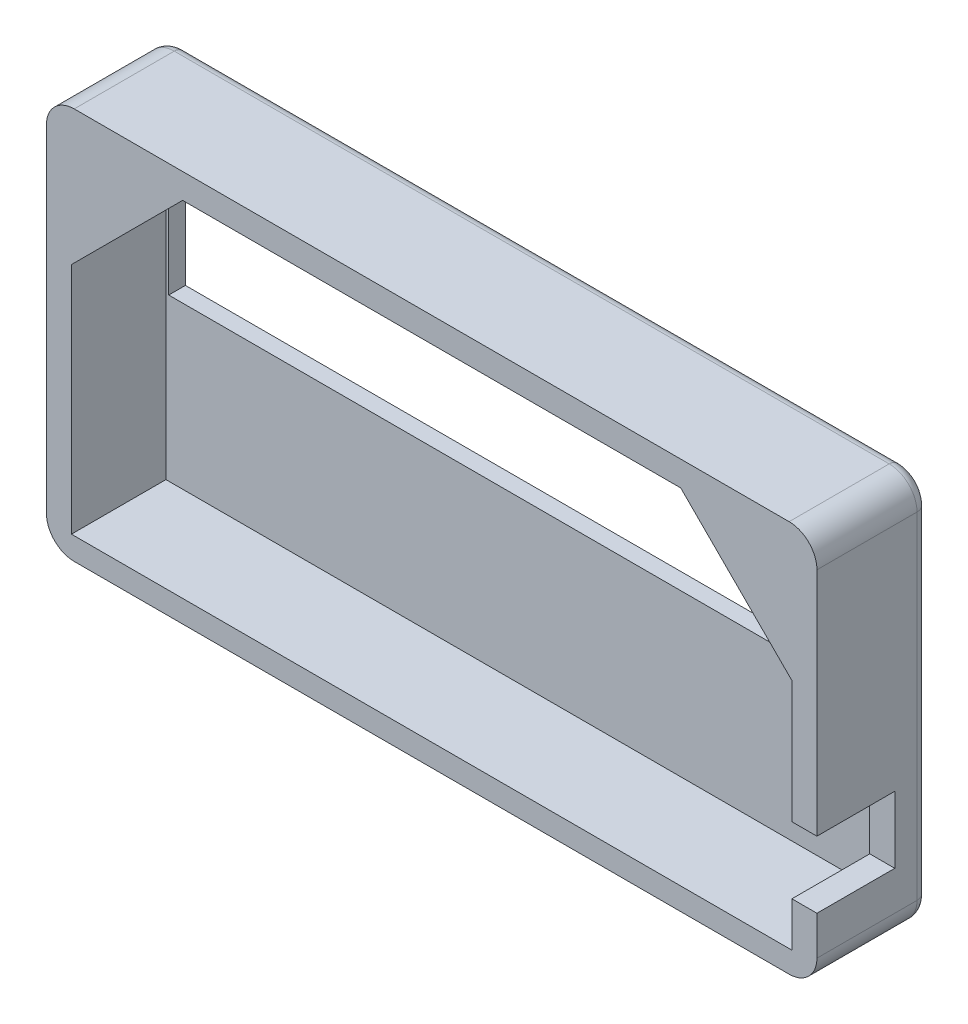
SolidWorks part; units mm, degrees
ref_plane "Front Plane" through (0, 0, 0) normal (0, 0, 1) x (1, 0, 0)
ref_plane "Top Plane" through (0, 0, 0) normal (0, 1, 0) x (1, 0, 0)
ref_plane "Right Plane" through (0, 0, 0) normal (1, 0, 0) x (0, 0, -1)
sketch "Sketch1" plane through (0, 0, 0) normal (0, 0, 1) x (1, 0, 0)
  line L1 (-80.2475, 9.5652) -> (48.3525, 9.5652)
  line L2 (-80.2475, 9.5652) -> (-80.2475, 42.0652)
  line L3 (-80.2475, 42.0652) -> (48.3525, 42.0652)
  line L4 (48.3525, 9.5652) -> (48.3525, 42.0652)
  line L5 (-80.2475, 9.5652) -> (48.3525, 42.0652) construction
  line L6 (-80.2475, 42.0652) -> (48.3525, 9.5652) construction
  line L7 (-85.2475, 47.0652) -> (53.3525, 47.0652)
  line L8 (-85.2475, 47.0652) -> (-85.2475, -23.4348)
  line L9 (-85.2475, -23.4348) -> (53.3525, -23.4348)
  line L10 (53.3525, 47.0652) -> (53.3525, -23.4348)
  point P0 (-15.9475, 25.8152)
  dimension "D1" = 128.6
  dimension "D2" = 32.5
  dimension "D3" = 5
  dimension "D4" = 5
  dimension "D5" = 5
  dimension "D6" = 33
extrude "Boss-Extrude1" add sketch "Sketch1" along normal blind 20
sketch "Sketch2" plane through (0, 0, 20) normal (0, 0, 1) x (1, 0, 0)
  line L1 (-80.7475, 42.5652) -> (48.8525, 42.5652)
  line L2 (-80.7475, 42.5652) -> (-80.7475, -19.4348)
  line L3 (-80.7475, -19.4348) -> (48.8525, -19.4348)
  line L4 (48.8525, 42.5652) -> (48.8525, -19.4348)
  line L5 (48.3525, 42.0652) -> (-80.2475, 42.0652) construction
  line L6 (-80.2475, 42.0652) -> (-80.2475, 9.5652) construction
  line L7 (48.3525, 9.5652) -> (48.3525, 42.0652) construction
  line L8 (-85.2475, -23.4348) -> (53.3525, -23.4348) construction
  dimension "D1" = 0.5
  dimension "D2" = 0.5
  dimension "D3" = 0.5
  dimension "D4" = 4
extrude "Cut-Extrude1" cut sketch "Sketch2" against normal offset from surface (17 mm away) 3 up to face at (-15.9475, 11.8152, 0)
fillet "Fillet2" radius 5 4 edges at (53.3525, 47.0652, 10) (-85.2475, 47.0652, 10) (-85.2475, -23.4348, 10) (53.3525, -23.4348, 10)
fillet "Fillet3" radius 2 8 edges at (51.888, 45.6008, 0) (53.3525, 11.8152, 0) (51.888, -21.9703, 0) (-15.9475, -23.4348, 0) (-83.783, -21.9703, 0) (-85.2475, 11.8152, 0) (-83.783, 45.6008, 0) (-15.9475, 47.0652, 0)
sketch "Sketch3" plane through (0, 0, 20) normal (0, 0, 1) x (1, 0, 0)
  line L0 (48.8525, -19.4348) -> (48.8525, 42.5652) construction
  line L1 (53.3525, -11.4348) -> (48.8525, -11.4348)
  line L2 (53.3525, -11.4348) -> (53.3525, 0.5652)
  line L3 (53.3525, 0.5652) -> (48.8525, 0.5652)
  line L4 (48.8525, -11.4348) -> (48.8525, 0.5652)
  line L5 (53.3525, -18.4348) -> (53.3525, 42.0652) construction
  line L6 (-80.7475, -19.4348) -> (48.8525, -19.4348) construction
  dimension "D1" = 12
  dimension "D2" = 8
extrude "Cut-Extrude2" cut sketch "Sketch3" against normal offset from surface (14 mm away) 3 up to face at (-15.9475, 25.8152, 3)
sketch "Sketch4" plane through (0, 0, 20) normal (0, 0, 1) x (1, 0, 0)
  line L0 (-60.7475, 42.5652) -> (-80.7475, 22.5652)
  line L1 (-80.7475, 42.5652) -> (48.8525, 42.5652) construction
  line L2 (-80.7475, 42.5652) -> (-80.7475, -19.4348) construction
  line L3 (-80.7475, 22.5652) -> (-80.7475, 42.5652)
  line L4 (-80.7475, 42.5652) -> (-60.7475, 42.5652)
  line L5 (48.8525, 22.5652) -> (48.8525, 42.5652)
  line L6 (48.8525, 42.5652) -> (-80.7475, 42.5652) construction
  line L7 (-15.9475, 42.5652) -> (-15.9475, 55.997) construction
  line L8 (28.8525, 42.5652) -> (48.8525, 22.5652)
  line L9 (48.8525, 42.5652) -> (28.8525, 42.5652)
  dimension "D1" = 20
  dimension "D2" = 45
extrude "Boss-Extrude2" add sketch "Sketch4" against normal offset from surface (2 mm away) 15 up to face at (-15.9475, 25.8152, 3)
